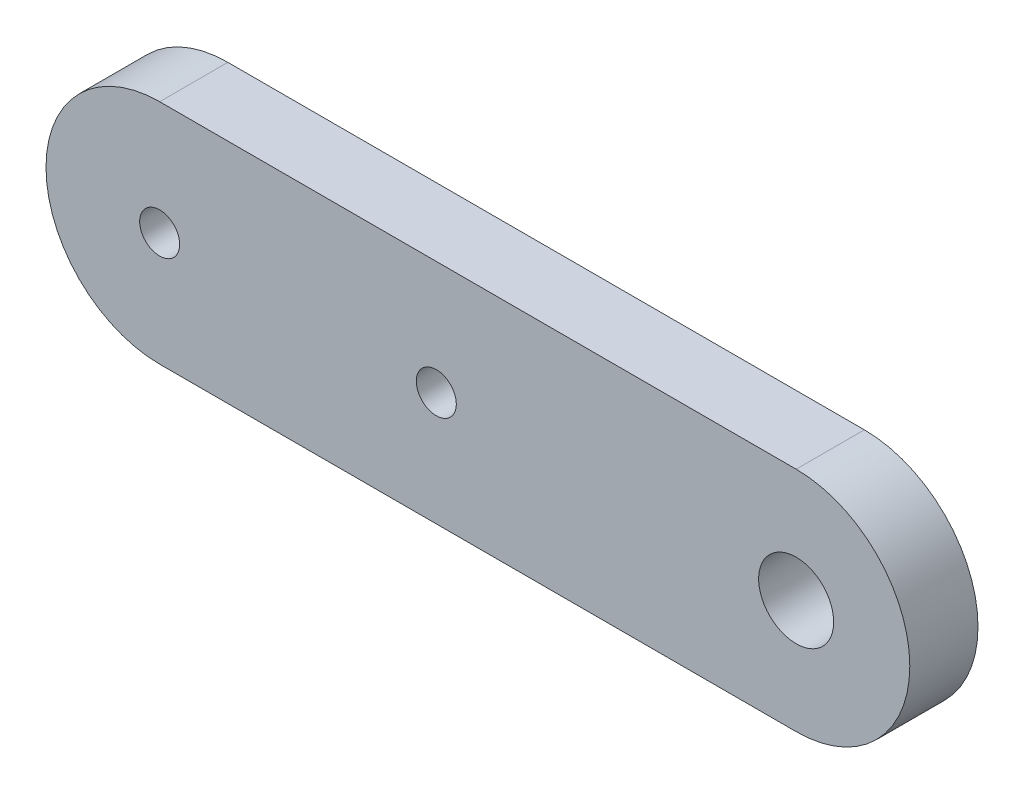
SolidWorks part; units mm, degrees
ref_plane "前视基准面" through (0, 0, 0) normal (0, 0, 1) x (1, 0, 0)
ref_plane "上视基准面" through (0, 0, 0) normal (0, 1, 0) x (1, 0, 0)
ref_plane "右视基准面" through (0, 0, 0) normal (1, 0, 0) x (0, 0, -1)
sketch "草图1" plane through (0, 0, 0) normal (0, 0, 1) x (1, 0, 0)
  line L0 (0, 0) -> (28, 0)
  line L1 (0, -10) -> (28, -10)
  line L2 (8, -5) -> (8, -1.0861) construction
  arc A0 (0, 0) -> (0, -10) centre (0, -5) ccw
  arc A1 (28, 0) -> (28, -10) centre (28, -5) cw
  circle A2 centre (0, -5) radius 0.88
  circle A3 centre (28, -5) radius 1.65
  circle A4 centre (12.17, -5) radius 0.88
  dimension "D2" = 28
  dimension "D3" = 20
  dimension "D4" = 12.17
  dimension "D1" = 10
extrude "凸台-拉伸1" add sketch "草图1" along normal blind 3
